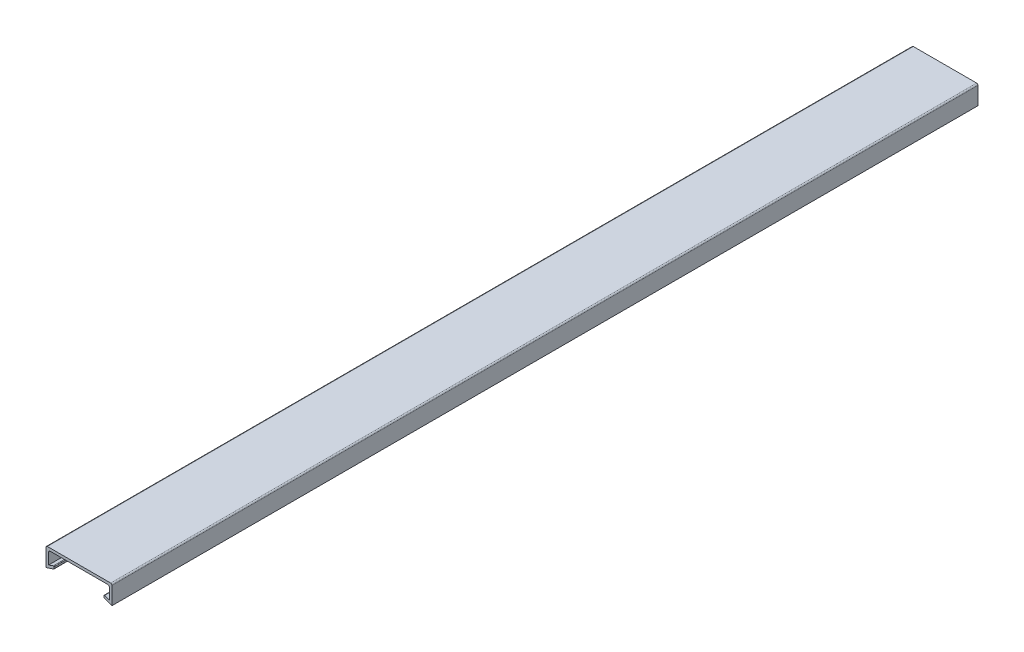
SolidWorks part; units mm, degrees
ref_plane "Alzado" through (0, 0, 0) normal (0, 0, 1) x (1, 0, 0)
ref_plane "Planta" through (0, 0, 0) normal (0, 1, 0) x (1, 0, 0)
ref_plane "Vista lateral" through (0, 0, 0) normal (1, 0, 0) x (0, 0, -1)
sketch "Croquis1" plane through (0, 0, 0) normal (0, 0, 1) x (1, 0, 0)
  line L0 (-9.3368, -6.0456) -> (-12.2, -7)
  line L1 (-12.2, -7) -> (-12.2, -0.5)
  line L2 (-11.7, 0) -> (11.7, 0)
  line L3 (12.2, -0.5) -> (12.2, -7)
  line L4 (0, 0) -> (0, -6.5) construction
  line L5 (9.2, -5.2775) -> (9.2, -5.8558)
  line L6 (9.3368, -6.0456) -> (12.2, -7)
  line L7 (11.2, -5.6667) -> (11.2, -1.5)
  line L8 (10.7, -1) -> (-10.7, -1)
  line L9 (-11.2, -1.5) -> (-11.2, -5.6667)
  line L10 (-11.2, -5.6667) -> (-9.4632, -5.0877)
  line L11 (-9.2, -5.2775) -> (-9.2, -5.8558)
  line L12 (11.2, -5.6667) -> (9.4632, -5.0877)
  arc A0 (11.7, 0) -> (12.2, -0.5) centre (11.7, -0.5) cw
  arc A1 (11.2, -1.5) -> (10.7, -1) centre (10.7, -1.5) ccw
  arc A2 (-10.7, -1) -> (-11.2, -1.5) centre (-10.7, -1.5) ccw
  arc A3 (-12.2, -0.5) -> (-11.7, 0) centre (-11.7, -0.5) cw
  arc A4 (9.2, -5.8558) -> (9.3368, -6.0456) centre (9.4, -5.8558) ccw
  arc A5 (9.2, -5.2775) -> (9.4632, -5.0877) centre (9.4, -5.2775) cw
  arc A6 (-9.3368, -6.0456) -> (-9.2, -5.8558) centre (-9.4, -5.8558) ccw
  arc A7 (-9.4632, -5.0877) -> (-9.2, -5.2775) centre (-9.4, -5.2775) cw
  point P13 (0, 0)
  point P19 (12.2, 0)
  point P26 (-12.2, 0)
  point P29 (9.2, -6)
  point P32 (9.2, -5)
  point P35 (-9.2, -6)
  point P38 (-9.2, -5)
  dimension "D9" = 0.5
  dimension "D10" = 0.2
  dimension "D2" = 1
  dimension "D3" = 1
  dimension "D4" = 1
  dimension "D5" = 24.4
  dimension "D6" = 3
  dimension "D7" = 2
  dimension "D8" = 1
  dimension "D11" = 7
extrude "Saliente-Extruir1" add sketch "Croquis1" along normal mid plane 320
